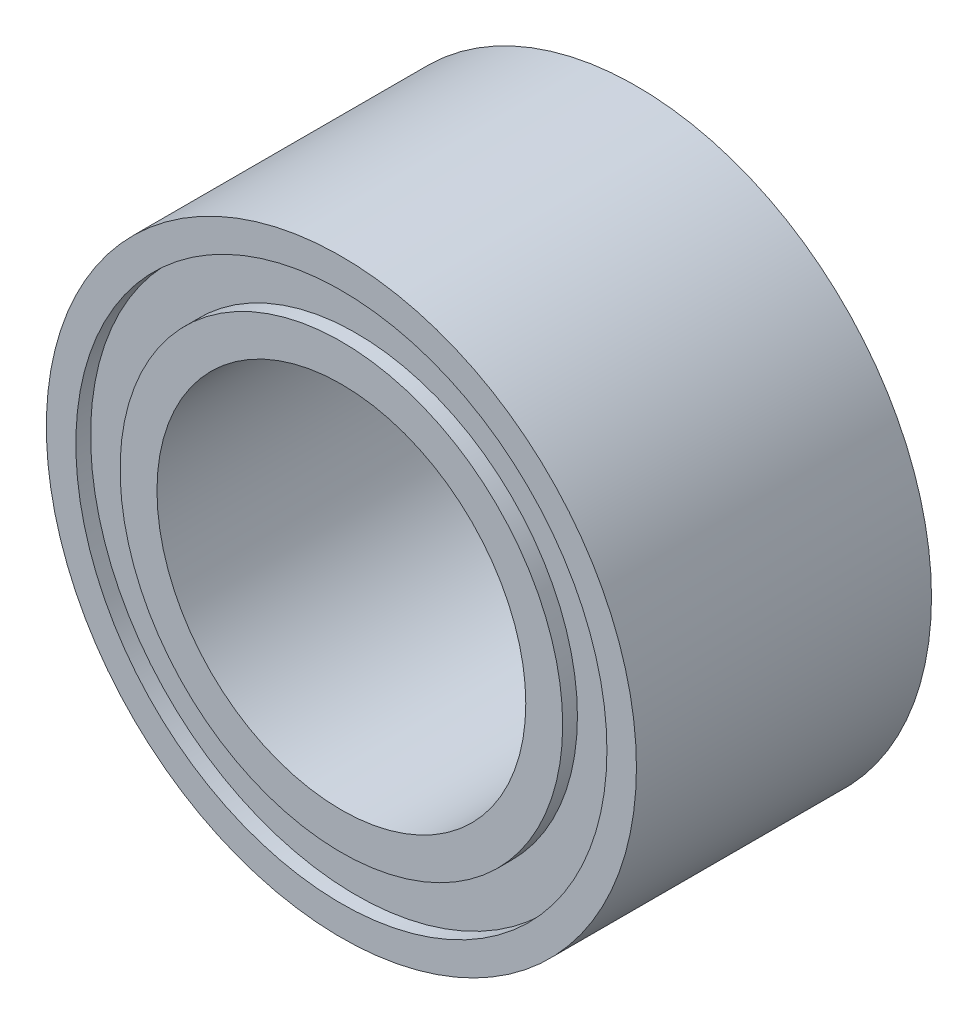
SolidWorks part; units mm, degrees
ref_plane "Front Plane" through (0, 0, 0) normal (0, 0, 1) x (1, 0, 0)
ref_plane "Top Plane" through (0, 0, 0) normal (0, 1, 0) x (1, 0, 0)
ref_plane "Right Plane" through (0, 0, 0) normal (1, 0, 0) x (0, 0, -1)
sketch "Sketch1" plane through (0, 0, 0) normal (0, 0, 1) x (1, 0, 0)
  circle A0 centre (0, 0) radius 5.08
  circle A1 centre (0, 0) radius 3.175
  dimension "D1" = 10.16
  dimension "D2" = 6.35
extrude "Boss-Extrude1" add sketch "Sketch1" along normal blind 5.08 contours A0
sketch "Sketch2" plane through (0, 0, 5.08) normal (0, 0, 1) x (1, 0, 0)
  circle A0 centre (0, 0) radius 3.81
  circle A1 centre (0, 0) radius 4.572
  dimension "D1" = 7.62
  dimension "D2" = 0.762
extrude "Cut-Extrude1" cut sketch "Sketch2" against normal blind 0.254
ref_plane "Plane1" through (0, 0, 2.54) normal (0, 0, 1) x (1, 0, 0)
mirror "Mirror1" about plane through (0, 0, 2.54) normal (0, 0, 1) of "Cut-Extrude1"
